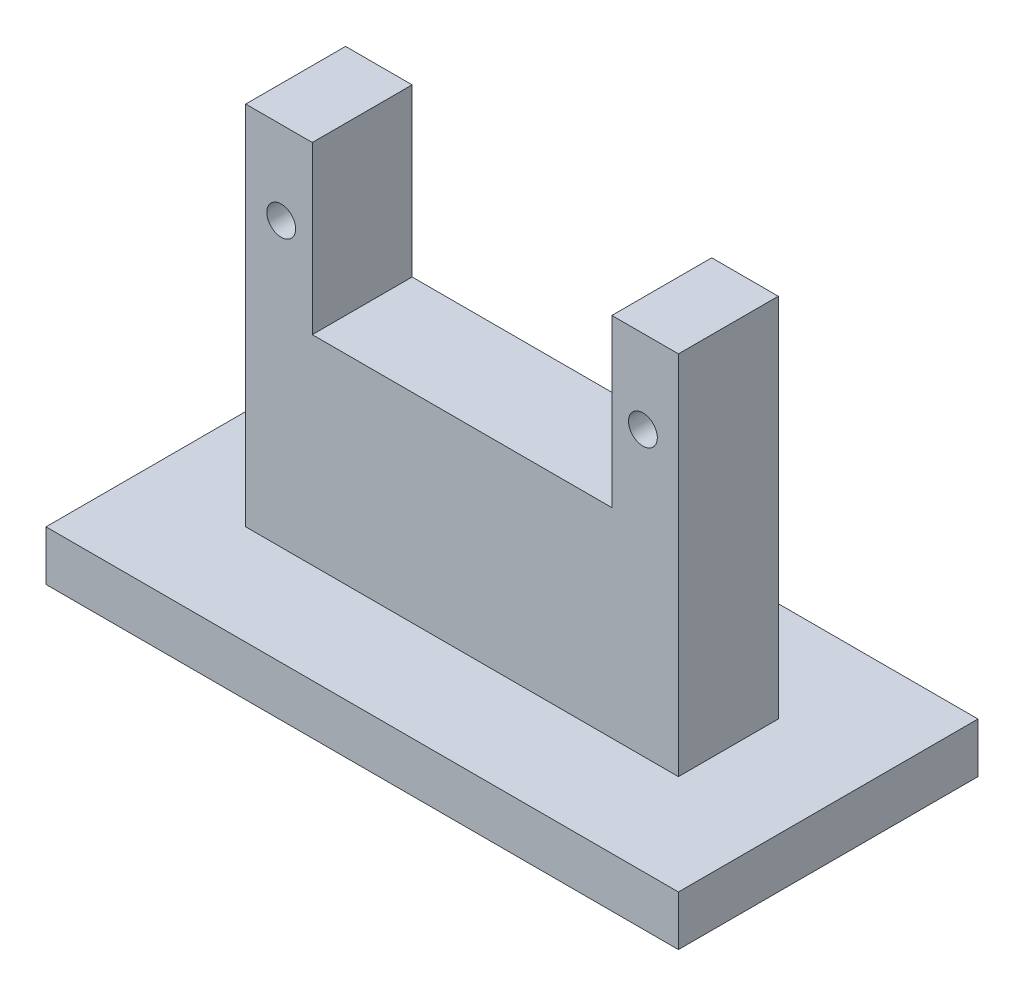
SolidWorks part; units mm, degrees
material "ABS"
ref_plane "Front Plane" through (0, 0, 0) normal (0, 0, 1) x (1, 0, 0)
ref_plane "Top Plane" through (0, 0, 0) normal (0, 1, 0) x (1, 0, 0)
ref_plane "Right Plane" through (0, 0, 0) normal (1, 0, 0) x (0, 0, -1)
sketch "Sketch6" plane through (0, 0, 0) normal (0, 0, 1) x (1, 0, 0)
  line L0 (-11.43, 19.05) -> (11.43, 19.05)
  line L1 (-16.51, 0) -> (16.51, 0)
  line L2 (-16.51, 0) -> (-16.51, 31.75)
  line L3 (-16.51, 31.75) -> (-11.43, 31.75)
  line L4 (16.51, 0) -> (16.51, 31.75)
  line L6 (-11.43, 31.75) -> (-11.43, 19.05)
  line L8 (11.43, 19.05) -> (11.43, 31.75)
  line L9 (11.43, 31.75) -> (16.51, 31.75)
  point P9 (0, 0)
  dimension "D1" = 33.02
  dimension "D2" = 12.7
  dimension "D3" = 22.86
  dimension "D4" = 19.05
extrude "Boss-Extrude4" add sketch "Sketch6" along normal blind 7.62
sketch "Sketch7" plane through (0, 0, 0) normal (0, 1, 0) x (1, 0, 0)
  line L8 (24.13, 7.62) -> (-24.13, 7.62)
  line L9 (24.13, -15.24) -> (24.13, 7.62)
  line L10 (-24.13, -15.24) -> (24.13, -15.24)
  line L11 (-24.13, 7.62) -> (-24.13, -15.24)
  line L12 (24.13, 7.62) -> (-24.13, 7.62)
  line L13 (24.13, -15.24) -> (24.13, 7.62)
  line L14 (-24.13, -15.24) -> (24.13, -15.24)
  line L15 (-24.13, 7.62) -> (-24.13, -15.24)
  dimension "D1" = 7.62
extrude "Boss-Extrude5" add sketch "Sketch7" along normal blind 3.81
hole_wizard "M2 Clearance Hole1" positions "Sketch8" profile "Sketch9" hole size "M2" standard "ANSI Metric" end condition through all
sketch "Sketch8" plane through (0, 0, 0) normal (0, 0, -1) x (-1, 0, 0)
  point P0 (-13.8, 25.4)
  point P3 (13.8, 25.4)
sketch "Sketch9" plane through (13.8, 25.4, 0) normal (1, 0, 0) x (0, 1, 0)
  line L0 (0, 0) -> (0, 15.24)
  line L1 (0, 15.24) -> (1.1, 15.24)
  line L2 (1.1, 15.24) -> (1.1, 0)
  line L5 (1.1, 0) -> (0, 0)
  line L11 (0, -6.35) -> (0, 107.95) construction
  dimension "Thru Hole Dia." = 2.2
  dimension "Thru Hole Depth" = 15.24
